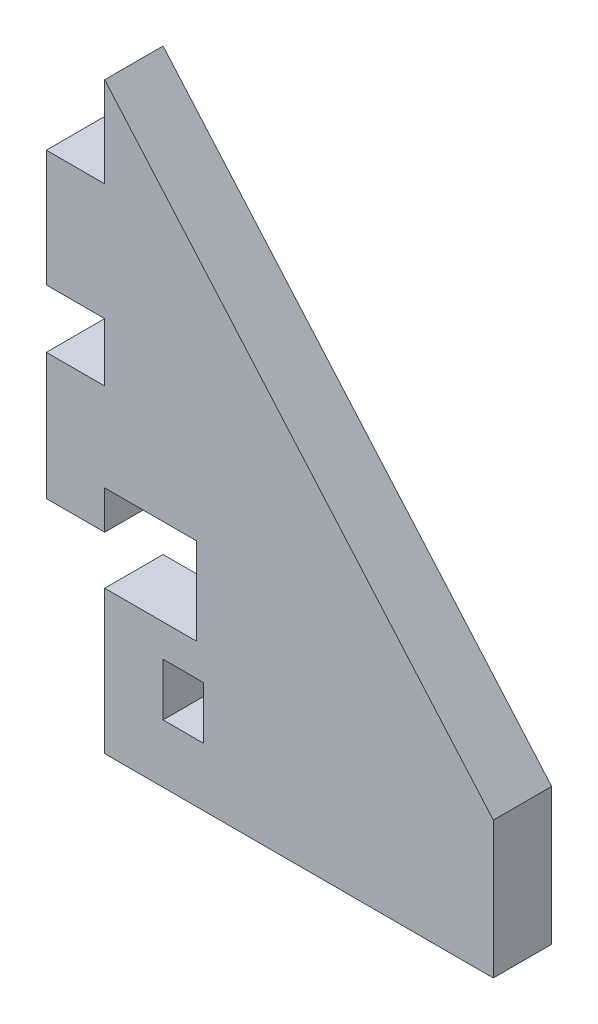
SolidWorks part; units mm, degrees
ref_plane "Front Plane" through (0, 0, 0) normal (0, 0, 1) x (1, 0, 0)
ref_plane "Top Plane" through (0, 0, 0) normal (0, 1, 0) x (1, 0, 0)
ref_plane "Right Plane" through (0, 0, 0) normal (1, 0, 0) x (0, 0, -1)
sketch "Sketch1" plane through (0, 0, 0) normal (0, 0, 1) x (1, 0, 0)
  line L0 (-12.3467, 38.1) -> (-18.6967, 38.1)
  line L1 (-18.6967, 38.1) -> (-18.6967, 25.4)
  line L2 (-18.6967, 25.4) -> (-12.3467, 25.4)
  line L3 (-12.3467, 25.4) -> (-12.3467, 19.05)
  line L4 (-12.3467, 19.05) -> (-18.6967, 19.05)
  line L5 (-18.6967, 19.05) -> (-18.6967, 5.2705)
  line L6 (-18.6967, 5.2705) -> (-12.3467, 5.2705)
  line L7 (-12.3467, 5.2705) -> (-12.3467, 9.4558)
  line L8 (-2.3467, 5.2705) -> (-2.3467, 0)
  line L9 (-5.7109, 0) -> (-12.3467, 0) construction
  line L10 (-2.3467, 0) -> (-12.3467, 0)
  line L11 (-12.3467, 0) -> (-12.3467, -15.5875)
  line L12 (-12.3467, -15.5875) -> (29.9353, -15.5875)
  line L13 (177.2366, -15.5875) -> (-12.3467, -15.5875) construction
  line L14 (29.9353, -15.5875) -> (29.9353, -0.7105)
  line L15 (29.9353, -0.7105) -> (-12.3467, 47.9125)
  line L16 (-12.3467, 47.9125) -> (-12.3467, 38.1)
  line L17 (-2.3467, 5.2705) -> (-2.3467, 9.4558)
  line L18 (-2.3467, 9.4558) -> (-12.3467, 9.4558)
  dimension "D1" = 10
extrude "Boss-Extrude1" add sketch "Sketch1" along normal blind 6.35
sketch "Sketch2" plane through (0, 0, 0) normal (0, 0, -1) x (-1, 0, 0)
  line L0 (12.3467, -15.5875) -> (-29.9353, -15.5875) construction
  line L1 (5.9967, -9.2375) -> (1.5967, -9.2375)
  line L2 (5.9967, -9.2375) -> (5.9967, -3.5175)
  line L3 (5.9967, -3.5175) -> (1.5967, -3.5175)
  line L4 (1.5967, -9.2375) -> (1.5967, -3.5175)
  line L5 (12.3467, 0) -> (12.3467, -15.5875) construction
  dimension "D1" = 5.72
  dimension "D2" = 4.4
  dimension "D3" = 6.35
  dimension "D4" = 6.35
extrude "Cut-Extrude1" cut sketch "Sketch2" against normal through all
